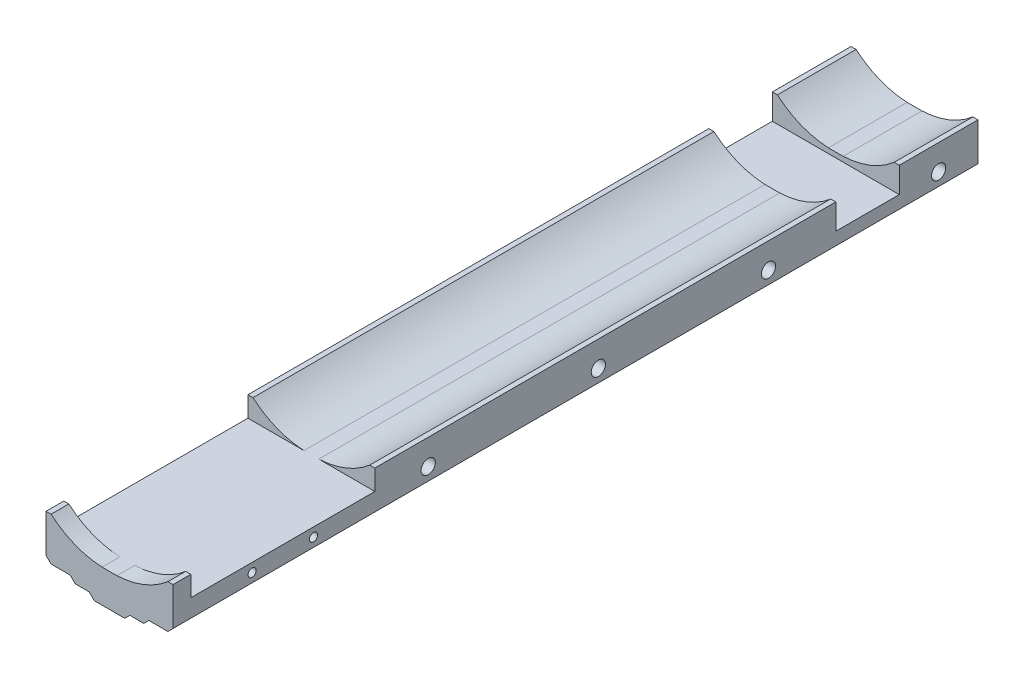
SolidWorks part; units mm, degrees
ref_plane "Front Plane" through (0, 0, 0) normal (0, 0, 1) x (1, 0, 0)
ref_plane "Top Plane" through (0, 0, 0) normal (0, 1, 0) x (1, 0, 0)
ref_plane "Right Plane" through (0, 0, 0) normal (1, 0, 0) x (0, 0, -1)
sketch "Sketch1" plane through (0, 0, 0) normal (0, 1, 0) x (1, 0, 0)
  line L1 (-25, -158.5) -> (25, -158.5)
  line L2 (-25, -158.5) -> (-25, 158.5)
  line L4 (25, -158.5) -> (25, 158.5)
  line L5 (-25, -158.5) -> (25, 158.5) construction
  line L6 (-25, 158.5) -> (25, -158.5) construction
  line L7 (-25, 158.5) -> (25, 158.5)
  point P0 (0, 0)
  dimension "D1" = 317
extrude "Boss-Extrude1" add sketch "Sketch1" along normal blind 7 contours L2 L7 L4 L1
sketch "Sketch2" plane through (0, 0, 158.5) normal (0, 0, 1) x (1, 0, 0)
  line L0 (25, 0) -> (25, 15)
  line L1 (-25, 7) -> (25, 7) construction
  line L2 (-0.0475, 7) -> (-0.0475, 0)
  line L3 (-25, 0) -> (25, 0) construction
  line L4 (-0.0475, 0) -> (25, 0)
  line L5 (25, 15) -> (23, 15)
  arc A0 (23, 15) -> (-0.0475, 7) centre (1.4313, 39.939) cw
  dimension "D2" = 2
  dimension "D3" = 15
extrude "Boss-Extrude2" add sketch "Sketch2" against normal up to vertex (317 mm away)
mirror "Mirror1" about plane through (0, 0, 0) normal (1, 0, 0) of "Boss-Extrude2"
sketch "Sketch4" plane through (0, 7, 0) normal (0, 1, 0) x (1, 0, 0)
  line L0 (-25, 158.5) -> (-25, -158.5) construction
  line L1 (25, -151.5) -> (-25, -151.5)
  line L2 (25, -151.5) -> (25, -79)
  line L3 (25, -79) -> (-25, -79)
  line L4 (-25, -151.5) -> (-25, -79)
  line L6 (-2.91, -158.5) -> (2.91, -158.5) construction
  line L7 (25, 158.5) -> (25, -158.5) construction
  dimension "D1" = 72.5
  dimension "D2" = 7
extrude "Cut-Extrude2" cut sketch "Sketch4" along normal blind 15
sketch "Sketch5" plane through (0, 7, 0) normal (0, 1, 0) x (1, 0, 0)
  line L1 (-25, 127.5) -> (25, 127.5)
  line L2 (-25, 127.5) -> (-25, 102.5)
  line L3 (-25, 102.5) -> (25, 102.5)
  line L4 (25, 127.5) -> (25, 102.5)
  line L5 (-2.91, 158.5) -> (2.91, 158.5) construction
  line L8 (25, 158.5) -> (25, -79) construction
  line L10 (-25, 158.5) -> (-25, -79) construction
  dimension "D1" = 31
  dimension "D2" = 25
extrude "Cut-Extrude3" cut sketch "Sketch5" along normal blind 12.5 and the other way blind 2
sketch "Sketch6" plane through (-25, 0, 0) normal (-1, 0, 0) x (0, 0, 1)
  line L0 (79, 7) -> (79, 0) construction
  line L1 (158.5, 0) -> (-158.5, 0) construction
  line L2 (79, 3.5) -> (103.1667, 3.5) construction
  line L3 (103.1667, 3.5) -> (127.3333, 3.5) construction
  line L4 (127.3333, 3.5) -> (151.5, 3.5) construction
  line L5 (151.5, 7) -> (151.5, 0) construction
  line L6 (103.1667, 1.9) -> (99.3376, 1.9) construction
  line L7 (158.5, 0) -> (-158.5, 0) construction
  circle A0 centre (103.1667, 3.5) radius 1.6
  circle A1 centre (127.3333, 3.5) radius 1.6
  dimension "D1" = 3.2
  dimension "D2" = 1.9
extrude "Cut-Extrude4" cut sketch "Sketch6" against normal blind 4.5
sketch "Sketch7" plane through (25, 0, 0) normal (1, 0, 0) x (0, 0, -1)
  line L0 (127.5, 5) -> (158.5, 5) construction
  line L1 (143, 2.2) -> (134.6963, 2.2) construction
  line L2 (127.5, 15) -> (127.5, 5) construction
  line L4 (158.5, 15) -> (158.5, 0) construction
  line L5 (-158.5, 0) -> (158.5, 0) construction
  circle A0 centre (143, 5) radius 2.8
  point P4 (143, 5)
  dimension "D2" = 5.6
  dimension "D1" = 5
  dimension "D3" = 2.2
extrude "Cut-Extrude5" cut sketch "Sketch7" against normal blind 9.1
pattern_linear "LPattern2" count 4 spacing 67 along (0, 0, 1) of "Cut-Extrude5"
mirror "Mirror3" about plane through (0, 0, 0) normal (1, 0, 0) of "Cut-Extrude4", "Cut-Extrude5", "LPattern2"
sketch "Sketch8" plane through (0, 0, 158.5) normal (0, 0, 1) x (1, 0, 0)
  line L1 (23, -2) -> (15.5, -2)
  line L2 (15.5, -2) -> (13.5, -4)
  line L3 (13.5, -4) -> (8, -4)
  line L4 (8, -4) -> (6, -6)
  line L5 (6, -6) -> (0, -6)
  line L6 (0, -6) -> (0, 0)
  line L7 (0, 0) -> (25, 0)
  line L8 (23, -2) -> (25, 0)
  dimension "D1" = 2
  dimension "D2" = 2
  dimension "D3" = 135
  dimension "D4" = 2
  dimension "D5" = 135
  dimension "D6" = 135
  dimension "D7" = 5.5
  dimension "D8" = 7.5
extrude "Boss-Extrude3" add sketch "Sketch8" against normal up to vertex (317 mm away)
mirror "Mirror4" about plane through (0, 0, 0) normal (1, 0, 0) of "Boss-Extrude3"
